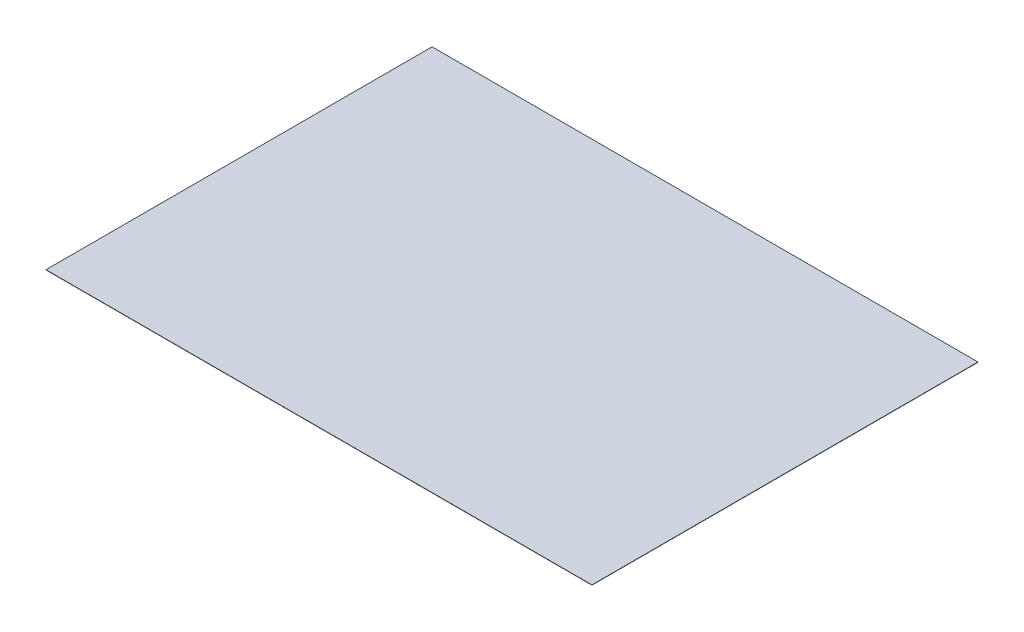
SolidWorks part; units mm, degrees
ref_plane "Front Plane" through (0, 0, 0) normal (0, 0, 1) x (1, 0, 0)
ref_plane "Top Plane" through (0, 0, 0) normal (0, 1, 0) x (1, 0, 0)
ref_plane "Right Plane" through (0, 0, 0) normal (1, 0, 0) x (0, 0, -1)
sketch "Sketch1" plane through (0, 0, 0) normal (0, 1, 0) x (1, 0, 0)
  line L1 (-210, 148.5) -> (210, 148.5)
  line L2 (-210, 148.5) -> (-210, -148.5)
  line L3 (-210, -148.5) -> (210, -148.5)
  line L4 (210, 148.5) -> (210, -148.5)
  line L5 (-210, 148.5) -> (210, -148.5) construction
  line L6 (-210, -148.5) -> (210, 148.5) construction
  point P0 (0, 0)
  dimension "D1" = 297
  dimension "D2" = 420
extrude "Boss-Extrude1" add sketch "Sketch1" along normal blind 0.2
